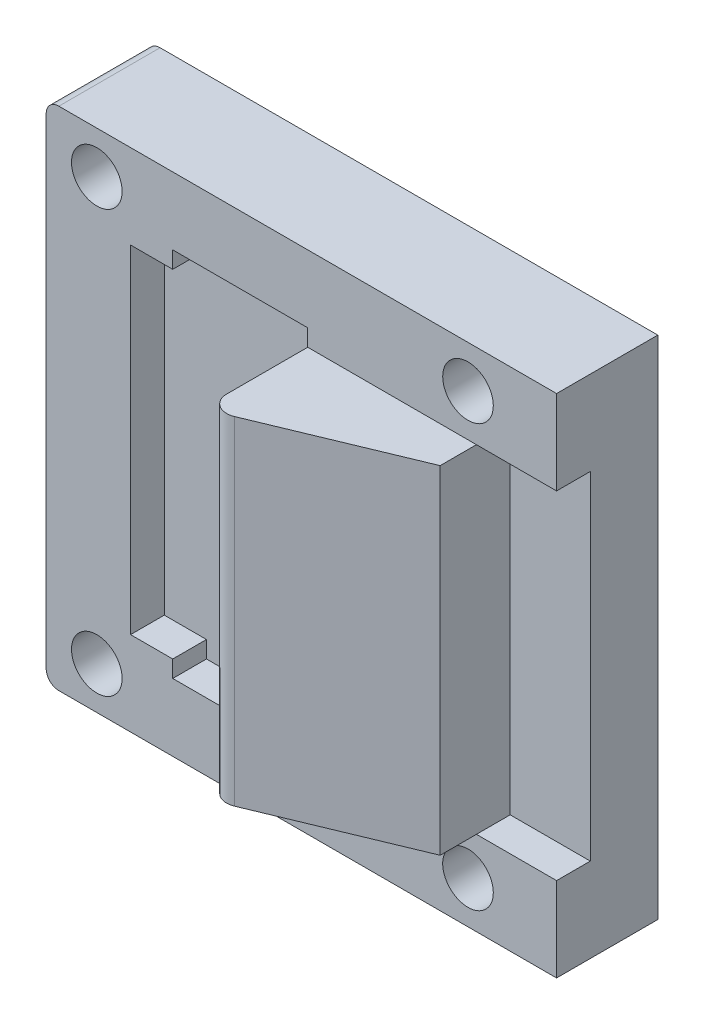
SolidWorks part; units mm, degrees
ref_plane "Ebene vorne" through (0, 0, 0) normal (0, 0, 1) x (1, 0, 0)
ref_plane "Ebene oben" through (0, 0, 0) normal (0, 1, 0) x (1, 0, 0)
ref_plane "Ebene rechts" through (0, 0, 0) normal (1, 0, 0) x (0, 0, -1)
sketch "Sketch1" plane through (0, 0, 0) normal (0, 0, 1) x (1, 0, 0)
  line L1 (15, -10) -> (-15, -10)
  line L2 (15, -10) -> (15, 10)
  line L3 (15, 10) -> (-15, 10)
  line L4 (-15, -10) -> (-15, 10)
  line L5 (15, -10) -> (-15, 10) construction
  line L6 (15, 10) -> (-15, -10) construction
  point P0 (0, 0)
  dimension "D1" = 20
  dimension "D2" = 30
extrude "Base Plate" add sketch "Sketch1" along normal blind 1
sketch "Sketch2" plane through (0, 0, 0) normal (0, 0, -1) x (1, 0, 0)
  line L1 (15, 10) -> (-15, 10)
  line L2 (15, 10) -> (15, 15)
  line L3 (15, 15) -> (-20, 15)
  line L5 (15, -10) -> (-15, -10)
  line L6 (15, -10) -> (15, -15)
  line L7 (15, -15) -> (-20, -15)
  line L11 (-15, -10) -> (-15, 10)
  line L13 (-20, -15) -> (-20, 15)
  dimension "D1" = 5
  dimension "D2" = 5
  dimension "D3" = 5
extrude "Side Walls" add sketch "Sketch2" against normal blind 6
sketch "Sketch3" plane through (0, 0, 1) normal (0, 0, 1) x (1, 0, 0)
  line L0 (15, 10) -> (-15, 10) construction
  line L1 (5.5, -10) -> (-4.5, -10)
  line L2 (5.5, -10) -> (5.5, 10)
  line L3 (5.5, 10) -> (-4.5, 10)
  line L4 (-4.5, -10) -> (-4.5, 10)
  line L5 (15, -10) -> (15, 10) construction
  line L6 (-15, -10) -> (15, -10) construction
  dimension "D1" = 10
  dimension "D2" = 9.5
extrude "Switch Block" add sketch "Sketch3" along direction (0, 0, -1) on the side of the normal offset from surface (7.15 mm away) 2.15
sketch "Sketch11" plane through (0, 0, 1) normal (0, 0, 1) x (1, 0, 0)
  line L1 (-15, -10) -> (-4.5, -10)
  line L2 (-15, -10) -> (-15, 10)
  line L3 (-15, 10) -> (-4.5, 10)
  line L4 (-4.5, -10) -> (-4.5, 10)
  line L5 (5.5, 10) -> (15, 10)
  line L6 (5.5, 10) -> (5.5, -10)
  line L7 (5.5, -10) -> (15, -10)
  line L8 (15, 10) -> (15, -10)
extrude "Thicker Body" add sketch "Sketch11" along normal offset from surface (3 mm away) 4 up to face at (-2.5, 0, 0)
sketch "Sketch5" plane through (0, 10, 0) normal (0, 1, 0) x (-1, 0, 0)
  line L0 (4.5, 8.15) -> (4.5, 12.3)
  line L1 (4.5, 12.3) -> (-5.5, 8.15)
  line L2 (-5.5, 8.15) -> (4.5, 8.15)
  dimension "D1" = 4.15
extrude "Switch Block Angle" add sketch "Sketch5" against normal up to surface (20 mm away) up to face at (0.5, -10, 7.075)
sketch "Sketch4" plane through (0, 0, 6) normal (0, 0, 1) x (1, 0, 0)
  line L0 (-20, -15) -> (-20, 15) construction
  line L2 (15, -10) -> (15, -15) construction
  line L3 (-15, 0) -> (-8.5625, 0) construction
  line L4 (-15, 10) -> (-15, -10) construction
  line L5 (15, -12.5) -> (1.31, -12.5) construction
  circle A0 centre (-17, -12.5) radius 1.5
  circle A1 centre (5, -12.5) radius 1.5
  circle A2 centre (5, 12.5) radius 1.5
  circle A3 centre (-17, 12.5) radius 1.5
  dimension "D1" = 3
  dimension "D2" = 3
  dimension "D5" = 10
extrude "M2 Screws" cut sketch "Sketch4" against normal up to surface (6 mm away) up to face at (-2.5, 0, 0)
fillet "Fillet1" radius 1 1 edges at (-4.5, 0, 12.3)
fillet "Fillet2" radius 0.5 1 edges at (15, -15, 3)
fillet "Fillet3" radius 0.5 1 edges at (15, 15, 3)
fillet "Fillet4" radius 0.75 1 edges at (-20, 15, 3)
fillet "Fillet5" radius 0.75 1 edges at (-20, -15, 3)
sketch "Sketch19" plane through (0, 0, 6) normal (0, 0, 1) x (1, 0, 0)
  line L0 (-15, -10) -> (-4.5, -10) construction
  line L1 (-12.5, 11) -> (-4.5, 11)
  line L2 (-12.5, 11) -> (-12.5, -11)
  line L3 (-12.5, -11) -> (-4.5, -11)
  line L4 (-4.5, 11) -> (-4.5, -11)
  line L5 (-4.5, 10) -> (-15, 10) construction
  dimension "D1" = 1
  dimension "D2" = 1
  dimension "D3" = 8
extrude "Space for LEaver" cut sketch "Sketch19" against normal up to surface (2 mm away) up to face at (-9.75, 0, 4)
sketch "Sketch20" plane through (0, 0, 0) normal (0, 0, -1) x (1, 0, 0)
  line L0 (5, 12.5) -> (5, -12.5) construction
  line L1 (7.5, 0) -> (6.3537, 0) construction
  line L2 (7.5, 2.5) -> (-20, 2.5)
  line L3 (7.5, 2.5) -> (7.5, -2.5)
  line L4 (7.5, -2.5) -> (-20, -2.5)
  line L5 (-20, 2.5) -> (-20, -2.5)
  line L6 (5, 0) -> (2.1521, 0) construction
  line L7 (-20, 14.25) -> (-20, -14.25) construction
  dimension "D1" = 2.5
  dimension "D2" = 5
extrude "Cut-Extrude1" cut sketch "Sketch20" against normal blind 2
sketch "Sketch21" plane through (0, 0, 6) normal (0, 0, 1) x (1, 0, 0)
  line L0 (15, -10) -> (15, 10) construction
  line L1 (10.25, 17.7976) -> (30.1052, 17.7976)
  line L2 (10.25, 17.7976) -> (10.25, -23.2908)
  line L3 (10.25, -23.2908) -> (30.1052, -23.2908)
  line L4 (30.1052, 17.7976) -> (30.1052, -23.2908)
  dimension "D1" = 4.75
extrude "Cut-Extrude2" cut sketch "Sketch21" against normal through all both and the other way through all
